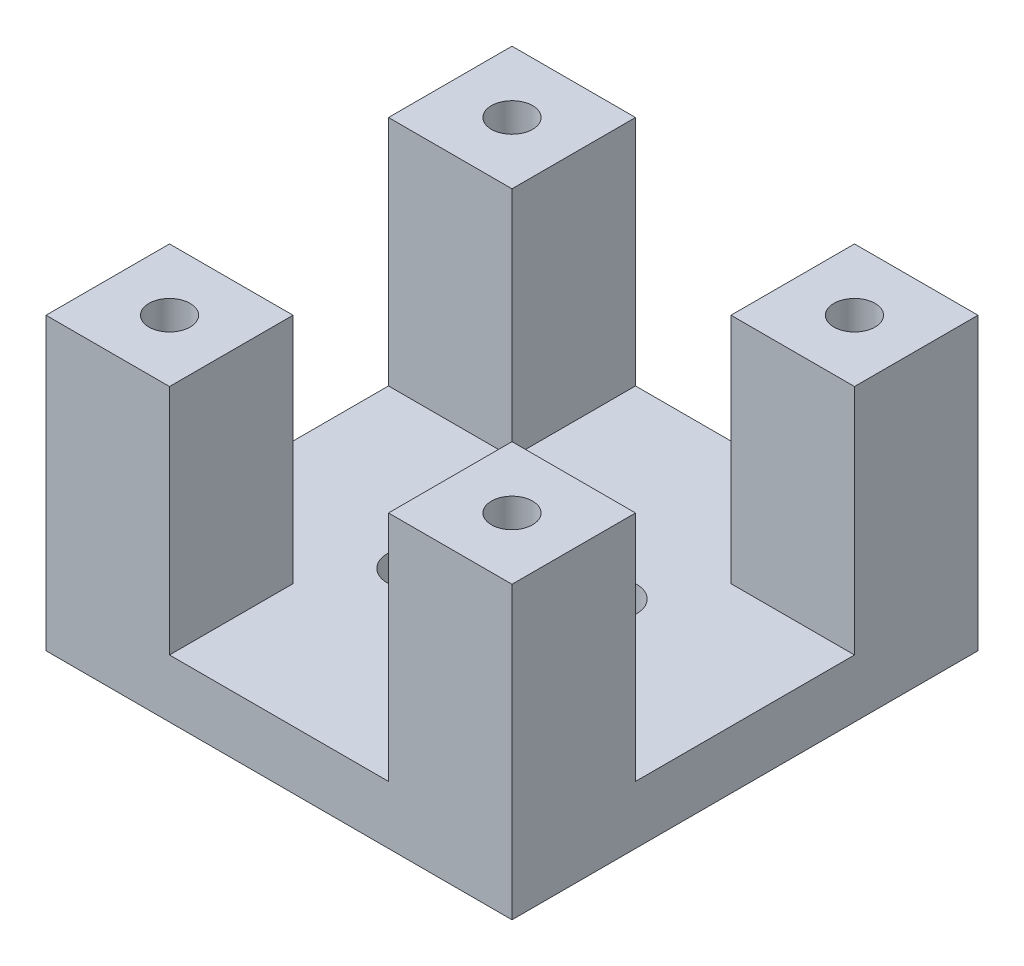
SolidWorks part; units mm, degrees
ref_plane "Front" through (0, 0, 0) normal (0, 0, 1) x (1, 0, 0)
ref_plane "Top" through (0, 0, 0) normal (0, 1, 0) x (1, 0, 0)
ref_plane "Right" through (0, 0, 0) normal (1, 0, 0) x (0, 0, -1)
sketch "Sketch1" plane through (0, 0, 0) normal (0, 1, 0) x (1, 0, 0)
  line L0 (0, 0) -> (0, 86.5638) construction
  line L1 (0, 0) -> (68.5951, 68.5951) construction
  line L2 (0, 0) -> (0, 15) construction
  line L3 (0, 0) -> (35.3553, 35.3553) construction
  line L5 (-48.1053, 48.1053) -> (48.1053, 48.1053)
  line L6 (-48.1053, 48.1053) -> (-48.1053, -48.1053)
  line L7 (-48.1053, -48.1053) -> (48.1053, -48.1053)
  line L8 (48.1053, 48.1053) -> (48.1053, -48.1053)
  circle A0 centre (0, 0) radius 10
  circle A1 centre (0, 15) radius 3.25
  circle A2 centre (35.3553, 35.3553) radius 4.25
  circle A3 centre (12.9904, 7.5) radius 3.25
  circle A4 centre (12.9904, -7.5) radius 3.25
  circle A5 centre (0, -15) radius 3.25
  circle A6 centre (-12.9904, -7.5) radius 3.25
  circle A7 centre (-12.9904, 7.5) radius 3.25
  circle A8 centre (35.3553, -35.3553) radius 4.25
  circle A9 centre (-35.3553, -35.3553) radius 4.25
  circle A10 centre (-35.3553, 35.3553) radius 4.25
  point P35 (-27.2126, 48.7202)
  point P36 (0, 0)
  dimension "D2" = 6.5
  dimension "D4" = 20
  dimension "D5" = 8.5
  dimension "D1" = 45
  dimension "D3" = 15
  dimension "D6" = 50
  dimension "D8" = 15
  dimension "D9" = 15
  dimension "D11" = 50
  dimension "D12" = 50
  dimension "D13" = 12.75
  dimension "D14" = 12.75
  dimension "D15" = 12.75
  dimension "D16" = 12.75
  dimension "D7" = 6
  dimension "D10" = 4
extrude "Boss-Extrude1" add sketch "Sketch1" along normal blind 60
sketch "Sketch4" plane through (0, 60, 0) normal (0, 1, 0) x (1, 0, 0)
  line L0 (-48.1053, 48.1053) -> (48.1053, 48.1053) construction
  line L1 (-22.6053, 48.1053) -> (22.6053, 48.1053)
  line L2 (-22.6053, 48.1053) -> (-22.6053, 22.6053)
  line L3 (-22.6053, -48.1053) -> (22.6053, -48.1053)
  line L4 (22.6053, 48.1053) -> (22.6053, 22.6053)
  line L5 (-48.1053, -48.1053) -> (48.1053, -48.1053) construction
  line L6 (-48.1053, 48.1053) -> (-48.1053, -48.1053) construction
  line L7 (-48.1053, 22.6053) -> (-22.6053, 22.6053)
  line L8 (-48.1053, 22.6053) -> (-48.1053, -22.6053)
  line L9 (-48.1053, -22.6053) -> (-22.6053, -22.6053)
  line L10 (48.1053, 22.6053) -> (48.1053, -22.6053)
  line L11 (48.1053, 48.1053) -> (48.1053, -48.1053) construction
  line L12 (-22.6053, -22.6053) -> (-22.6053, -48.1053)
  line L13 (22.6053, 22.6053) -> (48.1053, 22.6053)
  line L14 (22.6053, -22.6053) -> (22.6053, -48.1053)
  line L15 (22.6053, -22.6053) -> (48.1053, -22.6053)
  dimension "D1" = 12.75
  dimension "D2" = 12.75
  dimension "D3" = 12.75
  dimension "D4" = 12.75
extrude "Cut-Extrude2" cut sketch "Sketch4" against normal blind 48
sketch "Sketch2" plane through (0, 60, 0) normal (0, 1, 0) x (1, 0, 0)
  line L0 (0, 0) -> (-12.9904, 7.5) construction
  circle A0 centre (-12.9904, 7.5) radius 5.25
  circle A1 centre (0, 0) radius 5.4201 construction
  circle A2 centre (0, 15) radius 5.25
  circle A3 centre (12.9904, 7.5) radius 5.25
  circle A4 centre (12.9904, -7.5) radius 5.25
  circle A5 centre (0, -15) radius 5.25
  circle A6 centre (-12.9904, -7.5) radius 5.25
  dimension "D3" = 15
  dimension "D1" = 10.5
  dimension "D4" = 15
  dimension "D2" = 6
extrude "Cut-Extrude3" cut sketch "Sketch2" against normal blind 54
equation "\"motor mount pattern diameter\"= 30mm"
equation "\"motor mount m6 screw hole diameter\"= 6.5mm"
equation "\"coupler shaft hole diameter\"= 20mm"
equation "\"motor mount m6 screw socket head diameter\" = 10.5mm"
equation "\"motor mount m6 screw socket head depth\"= 6mm"
equation "\"mount to housing m8 screw diameter\"= 8.5mm"
equation "\"motor to housing distance\" = 60mm"
equation "\"mount to housing m8 screw post radius\" = ( 3 * \"mount to housing m8 screw diameter\" ) / 2"
equation "\"D2@Sketch1\"=\"motor mount m6 screw hole diameter\""
equation "\"D3@Sketch1\"=\"motor mount pattern diameter\"/2"
equation "\"D4@Sketch1\"=\"coupler shaft hole diameter\""
equation "\"D5@Sketch1\"=\"mount to housing m8 screw diameter\""
equation "\"mount to housing m8 pattern diameter\"= 100mm"
equation "\"D6@Sketch1\"=\"mount to housing m8 pattern diameter\"/2"
equation "\"D9@Sketch1\"=\"motor mount pattern diameter\"/2"
equation "\"D12@Sketch1\"=\"mount to housing m8 pattern diameter\"/2"
equation "\"D11@Sketch1\"=\"mount to housing m8 pattern diameter\"/2"
equation "\"D8@Sketch1\"=\"motor mount pattern diameter\"/2"
equation "\"D13@Sketch1\"=\"mount to housing m8 screw post radius\""
equation "\"D14@Sketch1\"=\"mount to housing m8 screw post radius\""
equation "\"D15@Sketch1\"=\"mount to housing m8 screw post radius\""
equation "\"D16@Sketch1\"=\"mount to housing m8 screw post radius\""
equation "\"plate thickness\" = \"motor mount m6 screw socket head depth\" + 6mm"
equation "\"D1@Boss-Extrude1\"=\"motor to housing distance\""
equation "\"D1@Sketch2\"=\"motor mount m6 screw socket head diameter\""
equation "\"D3@Sketch2\"=\"motor mount pattern diameter\"/2"
equation "\"D4@Sketch2\"=\"motor mount pattern diameter\"/2"
equation "\"D1@Sketch4\"=\"mount to housing m8 screw post radius\""
equation "\"D2@Sketch4\"=\"mount to housing m8 screw post radius\""
equation "\"D3@Sketch4\"=\"mount to housing m8 screw post radius\""
equation "\"D4@Sketch4\"=\"mount to housing m8 screw post radius\""
equation "\"D1@Cut-Extrude2\"=\"motor to housing distance\"-\"plate thickness\""
equation "\"D1@Cut-Extrude3\"=\"motor to housing distance\"-\"plate thickness\"+\"motor mount m6 screw socket head depth\""
